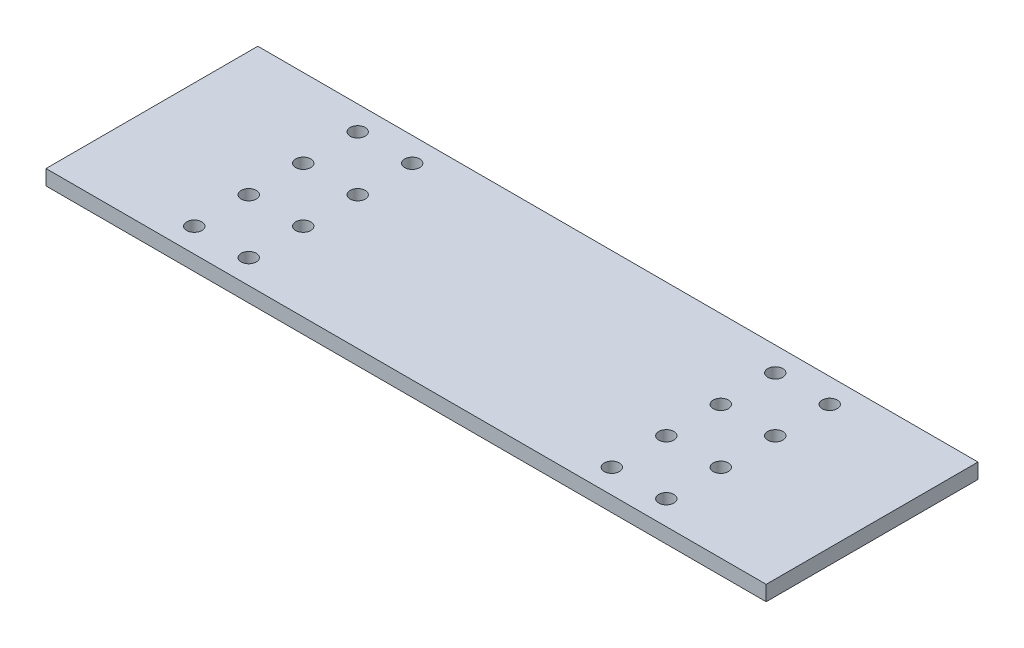
SolidWorks part; units mm, degrees
ref_plane "Front Plane" through (0, 0, 0) normal (0, 0, 1) x (1, 0, 0)
ref_plane "Top Plane" through (0, 0, 0) normal (0, 1, 0) x (1, 0, 0)
ref_plane "Right Plane" through (0, 0, 0) normal (1, 0, 0) x (0, 0, -1)
sketch "Sketch1" plane through (0, 0, 0) normal (0, 1, 0) x (1, 0, 0)
  line L1 (0, 0) -> (238, 0)
  line L2 (0, 0) -> (0, 70)
  line L3 (0, 70) -> (238, 70)
  line L4 (238, 0) -> (238, 70)
  circle A0 centre (41, 62) radius 2.5
  circle A1 centre (59, 62) radius 2.5
  circle A2 centre (41, 44) radius 2.5
  circle A3 centre (59, 44) radius 2.5
  circle A4 centre (197, 44) radius 2.5
  circle A5 centre (197, 62) radius 2.5
  circle A6 centre (179, 62) radius 2.5
  circle A7 centre (179, 44) radius 2.5
  circle A8 centre (197, 8) radius 2.5
  circle A9 centre (197, 26) radius 2.5
  circle A10 centre (179, 26) radius 2.5
  circle A11 centre (179, 8) radius 2.5
  circle A12 centre (59, 8) radius 2.5
  circle A13 centre (59, 26) radius 2.5
  circle A14 centre (41, 26) radius 2.5
  circle A15 centre (41, 8) radius 2.5
  dimension "D3" = 5
  dimension "D4" = 5
  dimension "D5" = 5
  dimension "D6" = 5
  dimension "D21" = 18
  dimension "D11" = 18
  dimension "D1" = 70
  dimension "D2" = 238
  dimension "D7" = 18
  dimension "D8" = 41
  dimension "D9" = 41
  dimension "D10" = 18
  dimension "D12" = 8
  dimension "D15" = 41
  dimension "D13" = 41
  dimension "D14" = 41
  dimension "D16" = 41
  dimension "D17" = 18
  dimension "D18" = 18
  dimension "D19" = 18
  dimension "D20" = 18
  dimension "D22" = 18
  dimension "D23" = 18
  dimension "D24" = 41
extrude "Boss-Extrude1" add sketch "Sketch1" along normal blind 5
